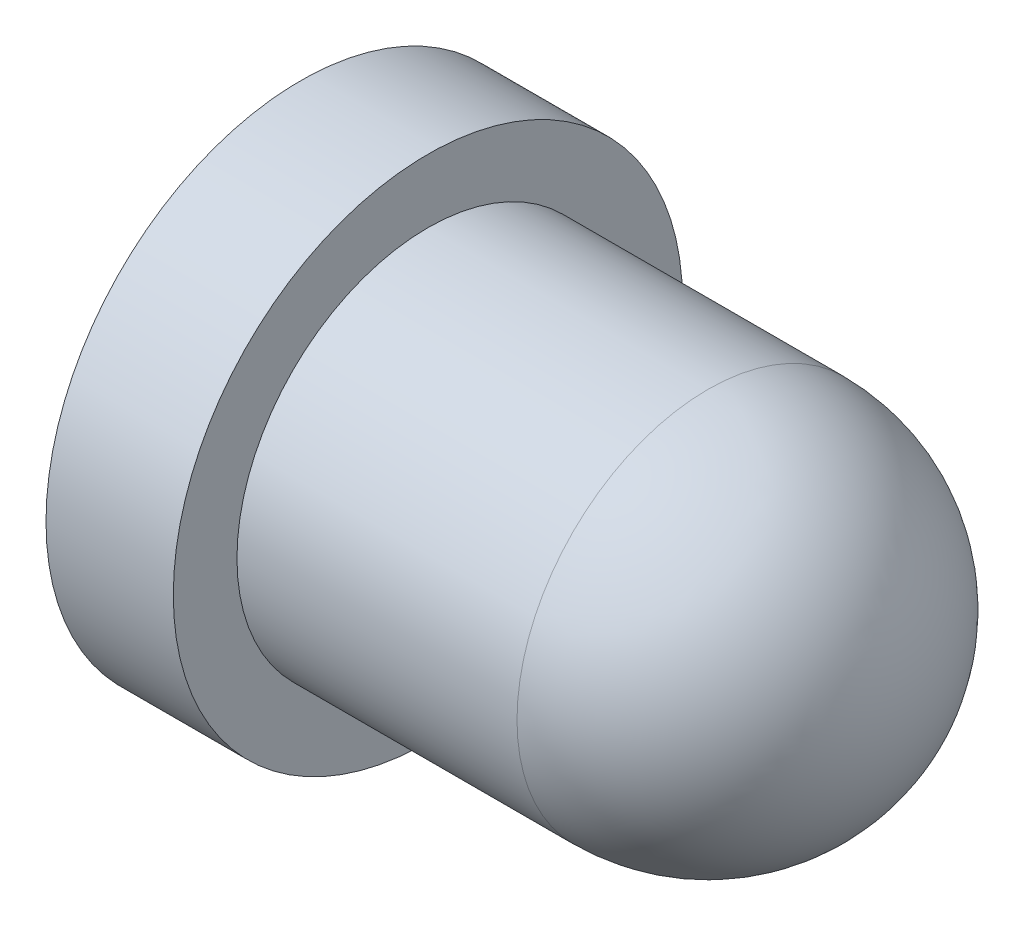
SolidWorks part; units mm, degrees
ref_plane "Front Plane" through (0, 0, 0) normal (0, 0, 1) x (1, 0, 0)
ref_plane "Top Plane" through (0, 0, 0) normal (0, 1, 0) x (1, 0, 0)
ref_plane "Right Plane" through (0, 0, 0) normal (1, 0, 0) x (0, 0, -1)
sketch "Sketch1" plane through (0, 0, 0) normal (1, 0, 0) x (0, 0, -1)
  circle A0 centre (0, 0) radius 2
  dimension "D1" = 4
extrude "Boss-Extrude1" add sketch "Sketch1" along normal blind 1
sketch "Sketch2" plane through (1, 0, 0) normal (1, 0, 0) x (0, 0, -1)
  circle A0 centre (0, 0) radius 1.5
  dimension "D1" = 3
extrude "Boss-Extrude2" add sketch "Sketch2" along normal blind 3.7
fillet "Fillet1" radius 1.5 1 edges at (4.7, 0, -1.5)
